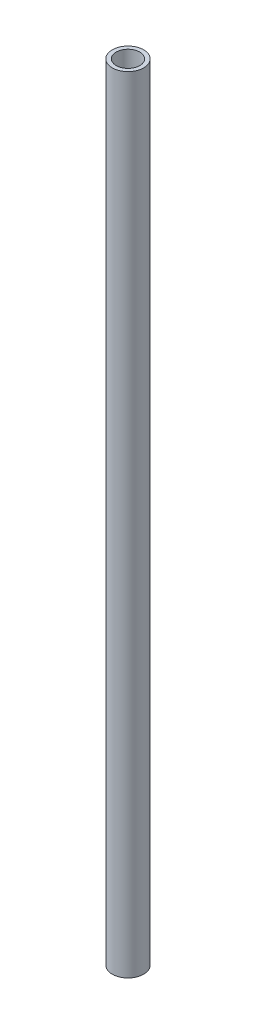
SolidWorks part; units mm, degrees
ref_plane "前视基准面" through (0, 0, 0) normal (0, 0, 1) x (1, 0, 0)
ref_plane "上视基准面" through (0, 0, 0) normal (0, 1, 0) x (1, 0, 0)
ref_plane "右视基准面" through (0, 0, 0) normal (1, 0, 0) x (0, 0, -1)
sketch "草图1" plane through (0, 0, 0) normal (0, 1, 0) x (1, 0, 0)
  circle A0 centre (0, 0) radius 3
  circle A1 centre (0, 0) radius 4
extrude "凸台-拉伸1" add sketch "草图1" along normal blind 200
